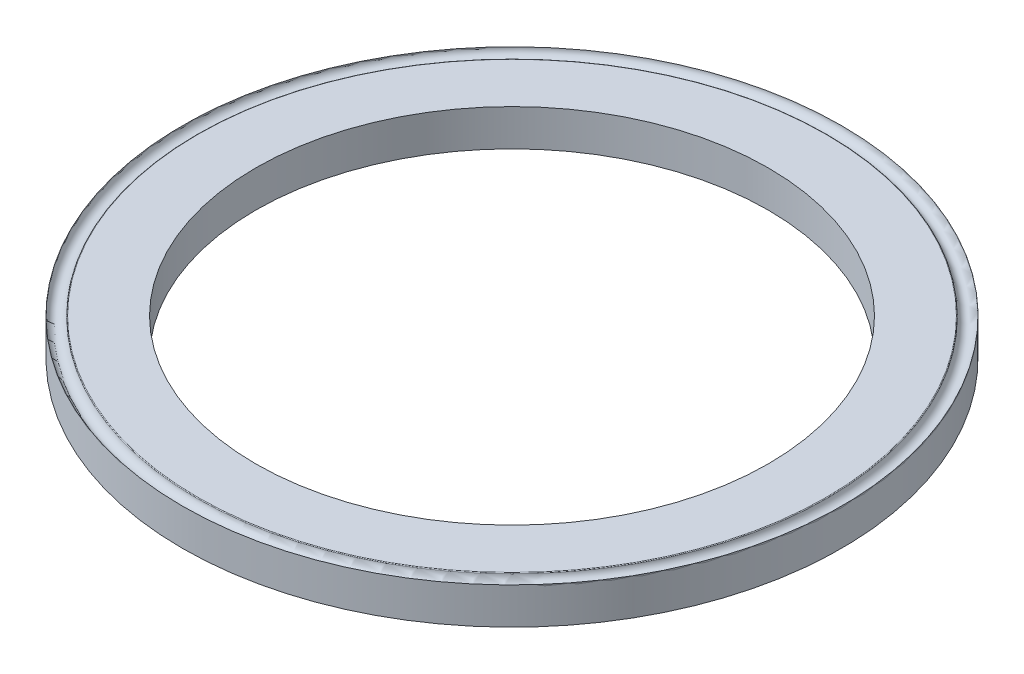
SolidWorks part; units mm, degrees
material "Chrome Stainless Steel"
ref_plane "Front Plane" through (0, 0, 0) normal (0, 0, 1) x (1, 0, 0)
ref_plane "Top Plane" through (0, 0, 0) normal (0, 1, 0) x (1, 0, 0)
ref_plane "Right Plane" through (0, 0, 0) normal (1, 0, 0) x (0, 0, -1)
sketch "Top Sketch" plane through (0, 0, 0) normal (0, 1, 0) x (1, 0, 0)
  circle A0 centre (0, 0) radius 3.5
  circle A1 centre (0, 0) radius 4.5
  dimension "InnerDia" = 7
  dimension "Width" = 1
extrude "Top" add sketch "Top Sketch" along normal mid plane 0.5
sketch "Crimp Sketch" plane through (0, 0, 0) normal (0, 0, 1) x (1, 0, 0)
  line L0 (4.5, 0.25) -> (-4.5, 0.25) construction
  line L1 (-4.5, 0.25) -> (-4.5, -0.25) construction
  line L3 (-4.5, 0.25) -> (-4.2905, 0.25)
  arc A0 (-4.5, 0.25) -> (-4.3004, 0.2409) centre (-4.4, 0.25) ccw
  arc A2 (-4.3004, 0.2409) -> (-4.2905, 0.25) centre (-4.2905, 0.24) cw
  dimension "Dia" = 0.2
  dimension "Fillet" = 0.01
revolve "Crimp" cut sketch "Crimp Sketch" angle 360 about axis through (0, 0.25, 0) along (0, -1, 0)
